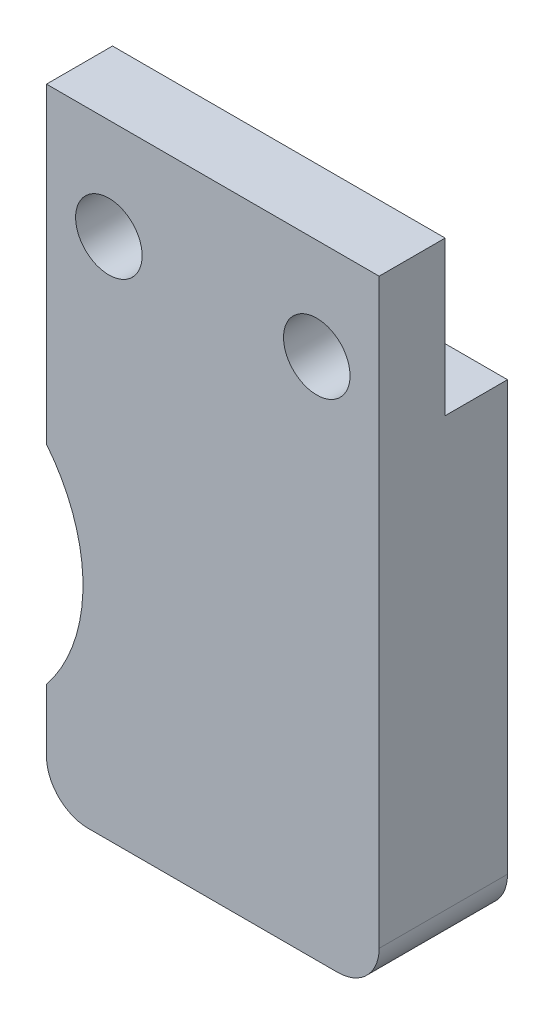
SolidWorks part; units mm, degrees
ref_plane "Front Plane" through (0, 0, 0) normal (0, 0, 1) x (1, 0, 0)
ref_plane "Top Plane" through (0, 0, 0) normal (0, 1, 0) x (1, 0, 0)
ref_plane "Right Plane" through (0, 0, 0) normal (1, 0, 0) x (0, 0, -1)
sketch "Sketch1" plane through (0, 0, 0) normal (0, 0, 1) x (1, 0, 0)
  line L0 (0, -20) -> (0, -50) construction
  line L1 (-8, -50) -> (8, -50)
  line L2 (-8, -50) -> (-8, -20)
  line L3 (-8, -20) -> (8, -20)
  line L4 (8, -50) -> (8, -20)
  line L5 (-8, -50) -> (8, -20) construction
  line L6 (-8, -20) -> (8, -50) construction
  circle A0 centre (5, -24.85) radius 1.6
  circle A2 centre (-5, -24.85) radius 1.6
  dimension "D3" = 3.2
  dimension "D7" = 5
  dimension "D8" = 4.85
  dimension "D6" = 3.2
  dimension "D1" = 30
  dimension "D2" = 16
  dimension "D4" = 5
  dimension "D5" = 4.85
extrude "Boss-Extrude1" add sketch "Sketch1" along normal blind 3.175
sketch "Sketch3" plane through (0, 0, 0) normal (0, 0, -1) x (-1, 0, 0)
  line L0 (8, -20) -> (8, -50) construction
  line L1 (-8, -50) -> (8, -50)
  line L2 (-8, -50) -> (-8, -27.4)
  line L3 (-8, -27.4) -> (8, -27.4)
  line L4 (8, -50) -> (8, -27.4)
  line L5 (-8, -20) -> (8, -20) construction
  dimension "D1" = 7.4
extrude "Boss-Extrude2" add sketch "Sketch3" along normal blind 3
fillet "Fillet1" radius 2 2 edges at (8, -50, 0.0875) (-8, -50, 0.0875)
sketch "Sketch4" plane through (0, 0, 3.175) normal (0, 0, 1) x (1, 0, 0)
  line L0 (-8, -20) -> (-8, -48) construction
  line L1 (-6, -50) -> (6, -50) construction
  line L2 (-8, -45) -> (-8, -35)
  arc A0 (-8, -45) -> (-8, -35) centre (-14.245, -40) ccw
  dimension "D2" = 8
  dimension "D1" = 5
  dimension "D3" = 10
extrude "Cut-Extrude1" cut sketch "Sketch4" against normal through all
